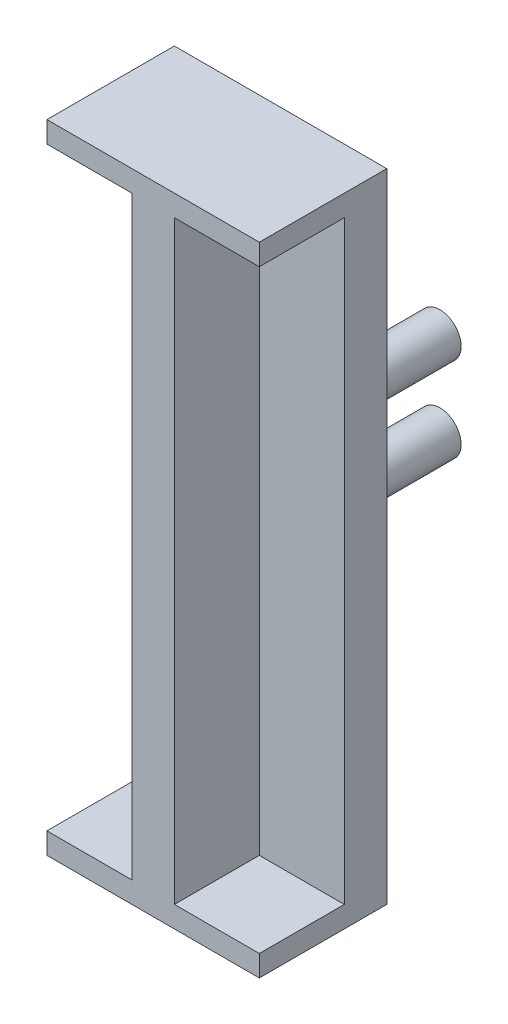
SolidWorks part; units mm, degrees
ref_plane "Front Plane" through (0, 0, 0) normal (0, 0, 1) x (1, 0, 0)
ref_plane "Top Plane" through (0, 0, 0) normal (0, 1, 0) x (1, 0, 0)
ref_plane "Right Plane" through (0, 0, 0) normal (1, 0, 0) x (0, 0, -1)
sketch "Sketch1" plane through (0, 0, 0) normal (0, 0, 1) x (1, 0, 0)
  line L1 (5, 15) -> (-5, 15)
  line L2 (5, 15) -> (5, -15)
  line L3 (5, -15) -> (-5, -15)
  line L4 (-5, 15) -> (-5, -15)
  line L5 (5, 15) -> (-5, -15) construction
  line L6 (5, -15) -> (-5, 15) construction
  point P0 (0, 0)
  dimension "D1" = 30
  dimension "D2" = 10
extrude "Boss-Extrude1" add sketch "Sketch1" along normal blind 2
sketch "Sketch2" plane through (0, 0, 2) normal (0, 0, 1) x (1, 0, 0)
  line L0 (-5, -15) -> (5, -15) construction
  line L1 (1.0662, 15.9932) -> (-1.0662, 15.9932)
  line L2 (1, 14) -> (1, -14)
  line L3 (1, -15) -> (-1, -15)
  line L5 (1.0662, 15.9932) -> (-1, -15) construction
  line L6 (1, -15) -> (-1.0662, 15.9932) construction
  line L7 (-5, 15) -> (-5, -15) construction
  line L8 (5, 15) -> (-5, 15)
  line L9 (5, 15) -> (5, 14)
  line L10 (5, 14) -> (1, 14)
  line L11 (-5, 15) -> (-5, 14)
  line L12 (5, 15) -> (-5, 14) construction
  line L13 (5, 14) -> (-5, 15) construction
  line L14 (1, -14) -> (5, -14)
  line L15 (-5, -14) -> (-1, -14)
  line L16 (-5, -14) -> (-5, -15)
  line L17 (-5, -15) -> (5, -15)
  line L18 (5, -14) -> (5, -15)
  line L19 (-5, -14) -> (5, -15) construction
  line L20 (-5, -15) -> (5, -14) construction
  line L21 (-1, 14) -> (-5, 14)
  line L22 (-1, 14) -> (-1, -14)
  point P0 (0, 0)
  point P12 (0, 14.5)
  point P20 (0, -14.5)
  dimension "D1" = 1
  dimension "D3" = 1
extrude "Boss-Extrude2" add sketch "Sketch2" along normal blind 4 contours L21 L22 L15 L5 L6 L7 L14 L2 L10 L9
sketch "Sketch4" plane through (0, 0, 0) normal (0, 0, -1) x (-1, 0, 0)
  line L0 (0, -2) -> (0, 15) construction
  line L1 (-5, 15) -> (5, 15) construction
  circle A0 centre (0, 2) radius 1
  circle A1 centre (0, -2) radius 1
  dimension "D1" = 2
  dimension "D3" = 2
  dimension "D2" = 4
  dimension "D4" = 2
extrude "Boss-Extrude3" add sketch "Sketch4" along normal blind 7.5
